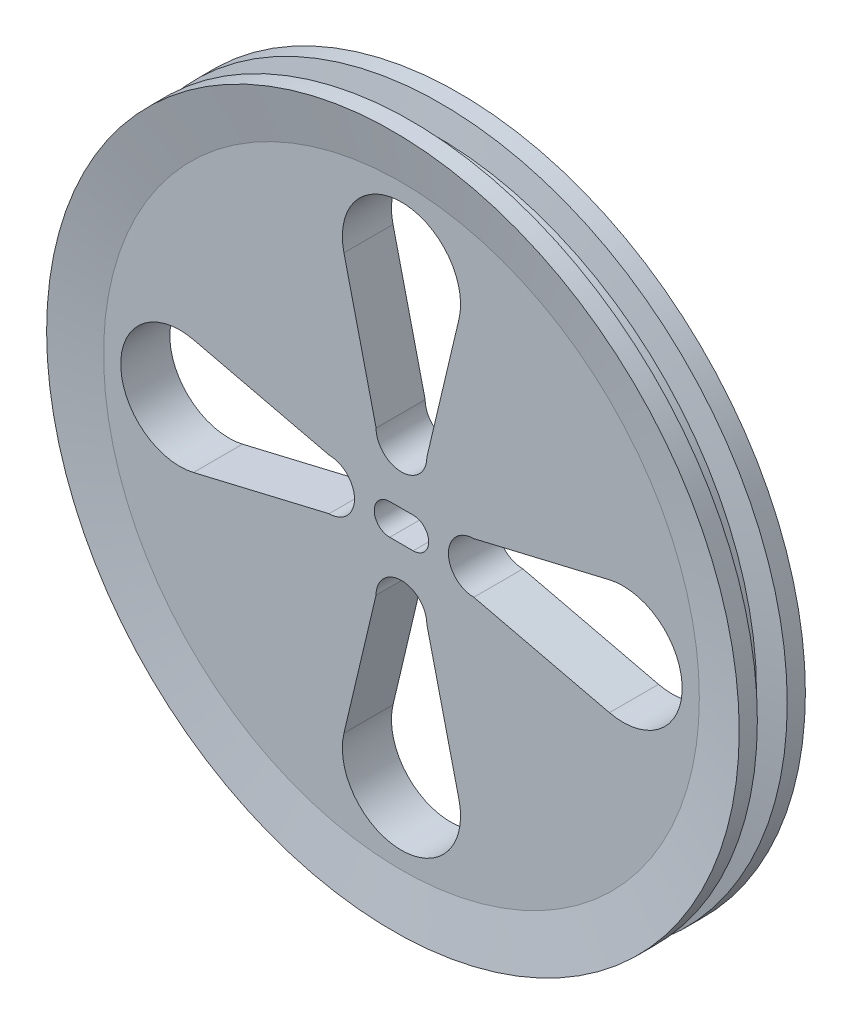
SolidWorks part; units mm, degrees
ref_plane "Front Plane" through (0, 0, 0) normal (0, 0, 1) x (1, 0, 0)
ref_plane "Top Plane" through (0, 0, 0) normal (0, 1, 0) x (1, 0, 0)
ref_plane "Right Plane" through (0, 0, 0) normal (1, 0, 0) x (0, 0, -1)
sketch "Sketch1" plane through (0, 0, 0) normal (1, 0, 0) x (0, 0, -1)
  line L2 (-2.921, 35.4495) -> (-3.937, 41.2115)
  line L3 (-3.937, 41.2115) -> (-1.778, 41.2115)
  line L4 (-1.778, 41.2115) -> (-1.2294, 38.1)
  line L5 (-1.2294, 38.1) -> (1.2294, 38.1)
  line L6 (0, 13.799) -> (0, -17.6922) construction
  line L13 (-2.921, 35.4495) -> (-2.921, 0)
  line L14 (-2.921, 0) -> (2.921, 0)
  line L15 (2.921, 35.4495) -> (2.921, 0)
  line L16 (2.921, 35.4495) -> (3.937, 41.2115)
  line L17 (3.937, 41.2115) -> (1.778, 41.2115)
  line L18 (1.778, 41.2115) -> (1.2294, 38.1)
  point P0 (0, 0)
  point P1 (1.1935, 38.1)
  point P7 (-1.1935, 38.1)
  point P8 (0, 38.1)
  point P12 (0, 0)
  point P13 (1.1935, 38.1)
  point P14 (2.2177, 0)
  point P15 (0, 0)
  point P17 (0, 38.1)
  dimension "D1" = 38.1
  dimension "D2" = 1.778
  dimension "D3" = 3.1115
  dimension "D4" = 2.159
  dimension "D5" = 100
  dimension "D6" = 2.921
revolve "Revolve1" add sketch "Sketch1" angle 360 about L14
sketch "Sketch2" plane through (0, 0, 2.921) normal (0, 0, -1) x (-1, 0, 0)
  line L0 (-1.397, 0) -> (1.397, 0) construction
  line L1 (-1.397, 1.8415) -> (1.397, 1.8415)
  line L2 (-1.397, -1.8415) -> (1.397, -1.8415)
  arc A0 (-1.397, 1.8415) -> (-1.397, -1.8415) centre (-1.397, 0) ccw
  arc A1 (1.397, -1.8415) -> (1.397, 1.8415) centre (1.397, 0) ccw
  point P3 (0, 0)
  point P9 (-3.2385, 0)
  point P10 (3.2385, 0)
  dimension "D1" = 3.683
  dimension "D2" = 6.477
sketch "Sketch4" plane through (0, 0, 2.921) normal (0, 0, -1) x (-1, 0, 0)
  line L2 (-3.0206, 8.6098) -> (-6.8442, 24.7491)
  line L3 (0, 21.7868) -> (0, -16.4384) construction
  line L4 (3.0206, 8.6098) -> (6.8442, 24.7491)
  arc A8 (-3.0206, 8.6098) -> (3.0206, 8.6098) centre (0, 8.6098) ccw
  arc A10 (6.8442, 24.7491) -> (-6.8442, 24.7491) centre (0, 26.3706) ccw
  point P1 (-6.9596, 27.3056)
  point P8 (-7.0758, 27.3056)
  point P10 (0, 6.4502)
  point P11 (-3.2997, 6.8569)
  point P12 (-7.0177, 26.288)
  point P13 (0, 0)
  point P14 (0, 8.6098)
extrude "Cut-Extrude3" cut sketch "Sketch4" along normal through all
extrude "Cut-Extrude4" cut sketch "Sketch2" along normal through all
pattern_circular "CirPattern1" count 4 over 360 about axis through (0, 0, 0) along (0, 0, 1) of "Cut-Extrude3"
